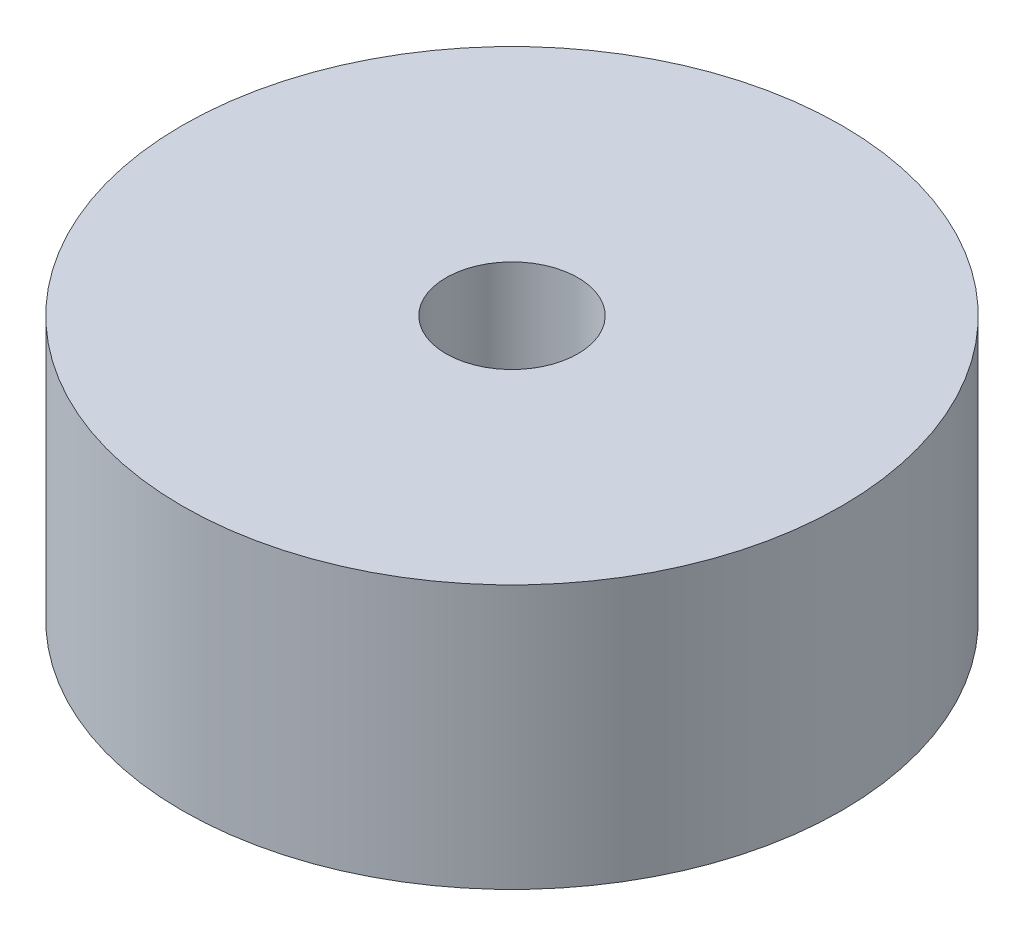
SolidWorks part; units mm, degrees
ref_plane "前基準面" through (0, 0, 0) normal (0, 0, 1) x (1, 0, 0)
ref_plane "上基準面" through (0, 0, 0) normal (0, 1, 0) x (1, 0, 0)
ref_plane "右基準面" through (0, 0, 0) normal (1, 0, 0) x (0, 0, -1)
sketch "草圖1" plane through (0, 0, 0) normal (0, 1, 0) x (1, 0, 0)
  circle A0 centre (0, 0) radius 0.5
  dimension "D1" = 1
extrude "伸長-薄件1" add sketch "草圖1" along normal blind 2 thin
